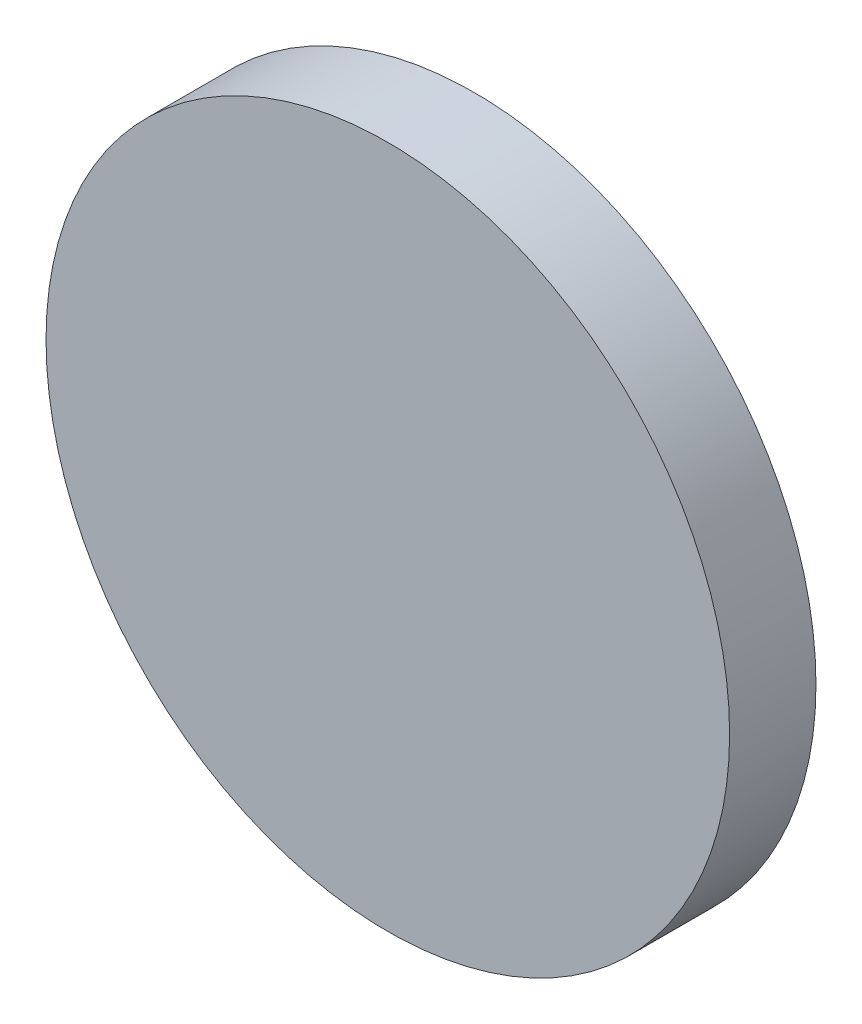
SolidWorks part; units mm, degrees
ref_plane "Front Plane" through (0, 0, 0) normal (0, 0, 1) x (1, 0, 0)
ref_plane "Top Plane" through (0, 0, 0) normal (0, 1, 0) x (1, 0, 0)
ref_plane "Right Plane" through (0, 0, 0) normal (1, 0, 0) x (0, 0, -1)
sketch "Sketch3" plane through (0, 0, 0) normal (0, 0, 1) x (1, 0, 0)
  circle A0 centre (0, 0) radius 47.5
  dimension "D1" = 95
extrude "Boss-Extrude2" add sketch "Sketch3" along normal blind 12
equation "\"LENGTH\" = 1000mm"
equation "\"WIDTH\" = 300mm"
equation "\"PLY\"= 12mm"
equation "\"CENTER_BRACE_LENGTH\" = 393mm"
equation "\"PANEL_WIDTH\"= \"LENGTH\" - \"CENTER_BRACE_LENGTH\" * 2 - \"PLY\" * 4"
equation "\"PANEL_SMALL_HEIGHT\" = 70mm"
equation "\"D1@Boss-Extrude2\"=\"PLY\""
